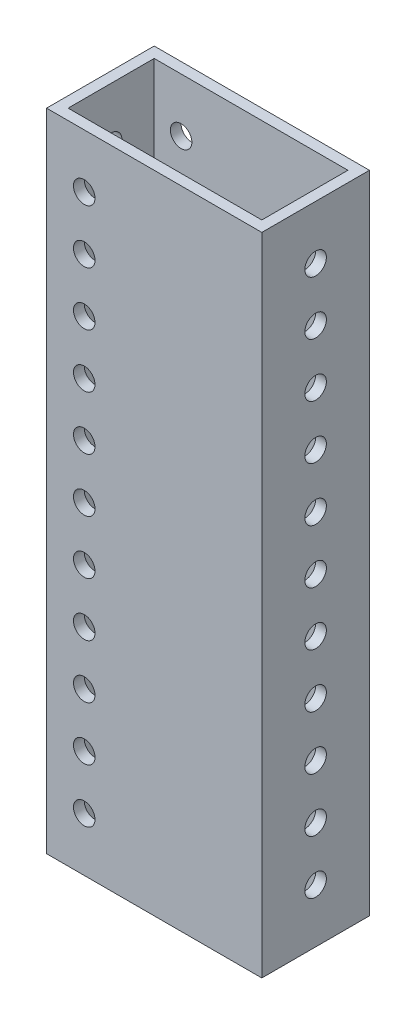
SolidWorks part; units mm, degrees
ref_plane "Front Plane" through (0, 0, 0) normal (0, 0, 1) x (1, 0, 0)
ref_plane "Top Plane" through (0, 0, 0) normal (0, 1, 0) x (1, 0, 0)
ref_plane "Right Plane" through (0, 0, 0) normal (1, 0, 0) x (0, 0, -1)
sketch "Sketch1" plane through (0, 0, 0) normal (0, 1, 0) x (1, 0, 0)
  line L1 (-59.9507, 17.7211) -> (-9.1507, 17.7211)
  line L2 (-59.9507, 17.7211) -> (-59.9507, -7.6789)
  line L3 (-59.9507, -7.6789) -> (-9.1507, -7.6789)
  line L4 (-9.1507, 17.7211) -> (-9.1507, -7.6789)
  line L5 (-59.9507, 17.7211) -> (-9.1507, -7.6789) construction
  line L6 (-59.9507, -7.6789) -> (-9.1507, 17.7211) construction
  line L7 (-57.4107, 15.1811) -> (-11.6907, 15.1811)
  line L8 (-57.4107, 15.1811) -> (-57.4107, -5.1389)
  line L9 (-57.4107, -5.1389) -> (-11.6907, -5.1389)
  line L10 (-11.6907, 15.1811) -> (-11.6907, -5.1389)
  line L11 (-57.4107, 15.1811) -> (-11.6907, -5.1389) construction
  line L12 (-57.4107, -5.1389) -> (-11.6907, 15.1811) construction
  point P0 (-34.5507, 5.0211)
  point P5 (-34.5507, 5.0211)
  dimension "D1" = 25.4
  dimension "D2" = 50.8
  dimension "D3" = 2.54
  dimension "D4" = 2.54
  dimension "D5" = 2.54
  dimension "D6" = 2.54
extrude "Boss-Extrude2" add sketch "Sketch1" along normal blind 152.4
sketch "Sketch2" plane through (-9.1507, 0, 0) normal (1, 0, 0) x (0, 0, -1)
  line L0 (-7.6789, 152.4) -> (17.7211, 152.4) construction
  line L1 (17.7211, 152.4) -> (17.7211, 0) construction
  circle A0 centre (5.0211, 139.7) radius 2.54
  circle A1 centre (5.0211, 127) radius 2.54
  circle A2 centre (5.0211, 114.3) radius 2.54
  circle A3 centre (5.0211, 101.6) radius 2.54
  circle A4 centre (5.0211, 88.9) radius 2.54
  circle A5 centre (5.0211, 76.2) radius 2.54
  circle A6 centre (5.0211, 63.5) radius 2.54
  circle A7 centre (5.0211, 50.8) radius 2.54
  circle A8 centre (5.0211, 38.1) radius 2.54
  circle A9 centre (5.0211, 25.4) radius 2.54
  circle A10 centre (5.0211, 12.7) radius 2.54
  dimension "D1" = 5.08
  dimension "D2" = 12.7
  dimension "D3" = 12.7
  dimension "D5" = 12.7
  dimension "D4" = 11
extrude "Cut-Extrude1" cut sketch "Sketch2" against normal blind 127
sketch "Sketch3" plane through (0, 0, -17.7211) normal (0, 0, -1) x (-1, 0, 0)
  line L0 (21.8507, 152.4) -> (21.8507, 0) construction
  line L1 (51.0607, 152.4) -> (51.0607, 0) construction
  line L2 (59.9507, 152.4) -> (59.9507, 0) construction
  line L3 (9.1507, 152.4) -> (59.9507, 152.4) construction
  line L4 (9.1507, 0) -> (59.9507, 0) construction
  line L5 (9.1507, 152.4) -> (9.1507, 0) construction
  line L6 (34.5507, 152.4) -> (34.5507, 0) construction
  circle A21 centre (51.0607, 139.7) radius 2.54
  circle A22 centre (51.0607, 127) radius 2.54
  circle A23 centre (51.0607, 114.3) radius 2.54
  circle A24 centre (51.0607, 101.6) radius 2.54
  circle A25 centre (51.0607, 88.9) radius 2.54
  circle A26 centre (51.0607, 76.2) radius 2.54
  circle A27 centre (51.0607, 63.5) radius 2.54
  circle A28 centre (51.0607, 50.8) radius 2.54
  circle A29 centre (51.0607, 38.1) radius 2.54
  circle A30 centre (51.0607, 25.4) radius 2.54
  circle A31 centre (51.0607, 12.7) radius 2.54
  dimension "D1" = 12.7
  dimension "D4" = 5.08
  dimension "D2" = 12.7
  dimension "D5" = 11
  dimension "D6" = 12.7
  dimension "D3" = 8.89
extrude "Cut-Extrude2" cut sketch "Sketch3" against normal through all
